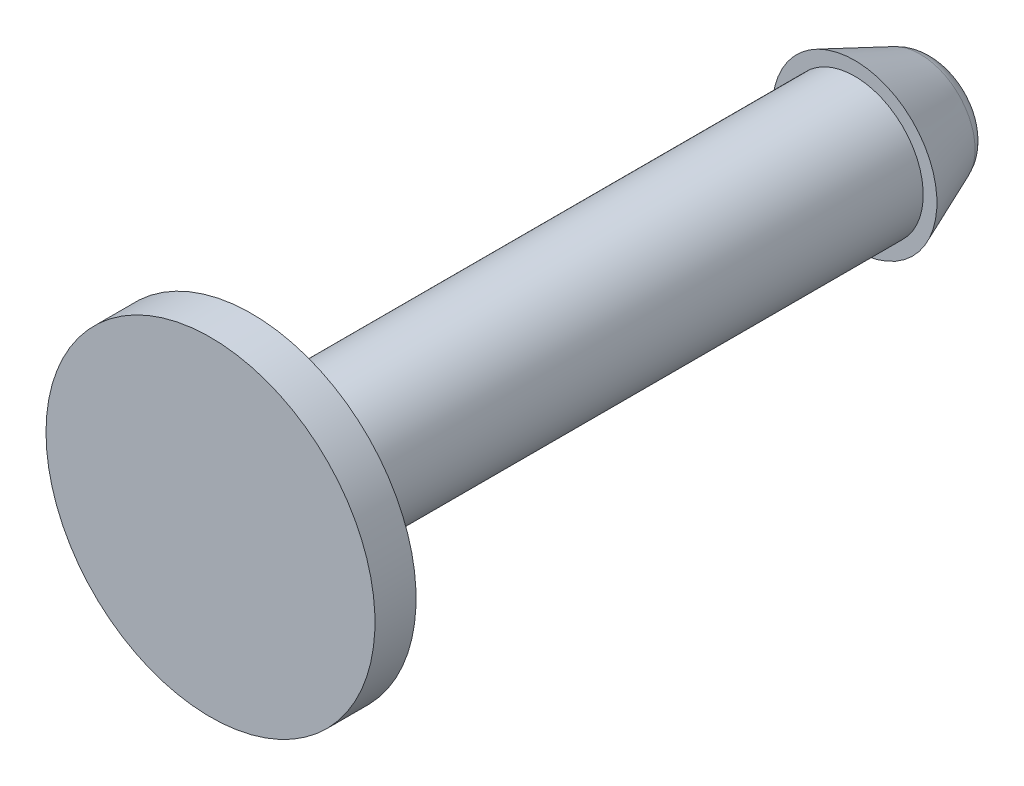
SolidWorks part; units mm, degrees
ref_plane "Спереди" through (0, 0, 0) normal (0, 0, 1) x (1, 0, 0)
ref_plane "Сверху" through (0, 0, 0) normal (0, 1, 0) x (1, 0, 0)
ref_plane "Справа" through (0, 0, 0) normal (1, 0, 0) x (0, 0, -1)
sketch "Эскиз1" plane through (0, 0, 0) normal (0, 1, 0) x (1, 0, 0)
  line L0 (0, 0) -> (6, 0)
  line L1 (6, 0) -> (6, 1.5)
  line L2 (6, 1.5) -> (2.5, 1.5)
  line L3 (2.5, 1.5) -> (2.5, 23.5)
  line L4 (2.5, 23.5) -> (3, 23.5)
  line L5 (3, 23.5) -> (1.75, 26.5)
  line L6 (1.75, 26.5) -> (0, 26.5)
  line L7 (0, 26.5) -> (0, 0)
  dimension "D1" = 6
  dimension "D2" = 2.5
  dimension "D3" = 1.5
  dimension "D4" = 3
  dimension "D5" = 1.75
  dimension "D6" = 0.5
  dimension "D7" = 26.5
revolve "Повернуть1" add sketch "Эскиз1" angle 360 about L7
fillet "Скругление1" radius 1 1 edges at (-1.75, 0, -26.5)
